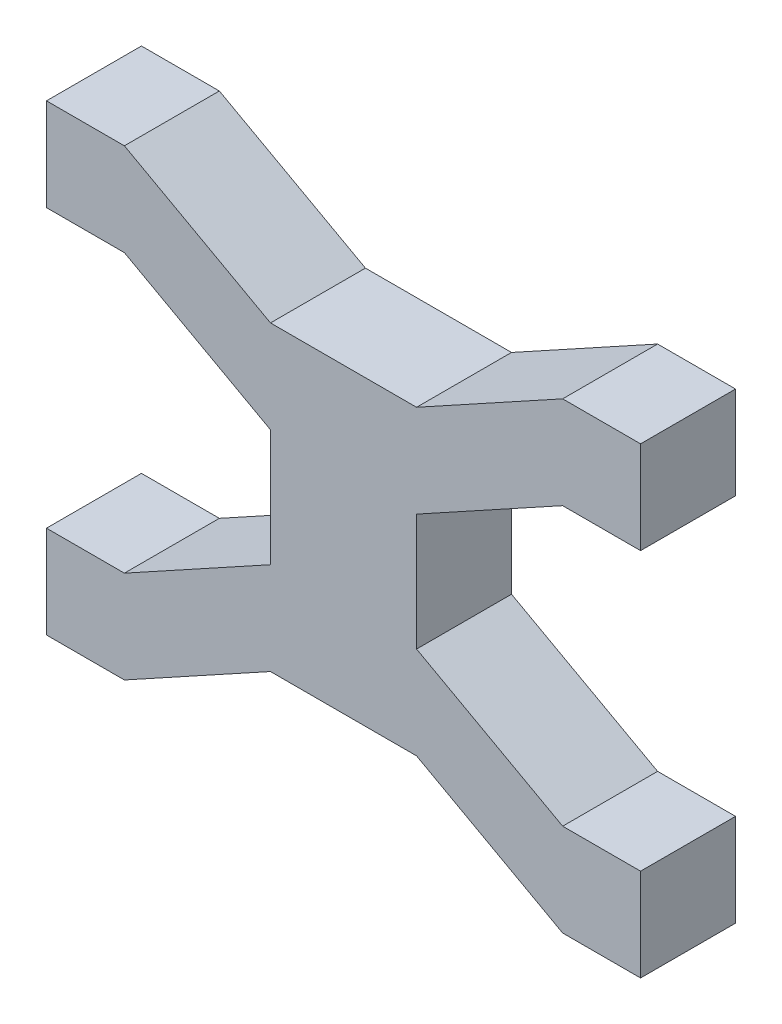
SolidWorks part; units mm, degrees
ref_plane "Ebene vorne" through (0, 0, 0) normal (0, 0, 1) x (1, 0, 0)
ref_plane "Ebene oben" through (0, 0, 0) normal (0, 1, 0) x (1, 0, 0)
ref_plane "Ebene rechts" through (0, 0, 0) normal (1, 0, 0) x (0, 0, -1)
sketch "Skizze1" plane through (0, 0, 0) normal (0, 0, 1) x (1, 0, 0)
  line L0 (0, 0) -> (72.418, 0) construction
  line L1 (30.5, 14.25) -> (30.5, 23.75)
  line L2 (30.5, 23.75) -> (22.5, 23.75)
  line L3 (30.5, 14.25) -> (22.5, 14.25)
  line L4 (30.5, 19) -> (15.2992, 19) construction
  line L5 (0, 0) -> (0, 31.2334) construction
  line L6 (30.5, 23.75) -> (22.5, 23.75)
  line L7 (30.5, 14.25) -> (22.5, 14.25)
  line L8 (30.5, -14.25) -> (22.5, -14.25)
  line L9 (30.5, -23.75) -> (22.5, -23.75)
  line L10 (30.5, -14.25) -> (22.5, -14.25)
  line L11 (30.5, -23.75) -> (22.5, -23.75)
  line L12 (30.5, -14.25) -> (30.5, -23.75)
  line L13 (22.5, 14.25) -> (7.5, 6)
  line L14 (22.5, 23.75) -> (7.5, 15.5)
  line L15 (22.5, -14.25) -> (7.5, -6)
  line L16 (22.5, -23.75) -> (7.5, -15.5)
  line L17 (7.5, -6) -> (7.5, 6)
  line L18 (7.5, 15.5) -> (-7.5, 15.5)
  line L19 (7.5, -15.5) -> (-7.5, -15.5)
  line L20 (-30.5, 19) -> (-15.2992, 19) construction
  line L21 (-7.5, -6) -> (-7.5, 6)
  line L22 (-22.5, -23.75) -> (-7.5, -15.5)
  line L23 (-22.5, -14.25) -> (-7.5, -6)
  line L24 (-22.5, 23.75) -> (-7.5, 15.5)
  line L25 (-22.5, 14.25) -> (-7.5, 6)
  line L26 (-30.5, -14.25) -> (-30.5, -23.75)
  line L27 (-30.5, -23.75) -> (-22.5, -23.75)
  line L28 (-30.5, -14.25) -> (-22.5, -14.25)
  line L29 (-30.5, -23.75) -> (-22.5, -23.75)
  line L30 (-30.5, -14.25) -> (-22.5, -14.25)
  line L31 (-30.5, 14.25) -> (-22.5, 14.25)
  line L32 (-30.5, 23.75) -> (-22.5, 23.75)
  line L33 (-30.5, 14.25) -> (-22.5, 14.25)
  line L34 (-30.5, 23.75) -> (-22.5, 23.75)
  line L35 (-30.5, 14.25) -> (-30.5, 23.75)
  point P23 (0, -15.5)
  point P24 (0, 15.5)
  dimension "D1" = 9.5
  dimension "D2" = 19
  dimension "D3" = 8
  dimension "D4" = 22.5
  dimension "D5" = 15
  dimension "D6" = 12
extrude "Aufsatz-Linear austragen1" add sketch "Skizze1" along normal blind 9.75 contours L35 L31 L25 L21 L23 L28 L26 L27 L22 L19 L16 L9 L12 L8 L15 L17 L13 L3 L1 L2 L14 L18 L24 L32
